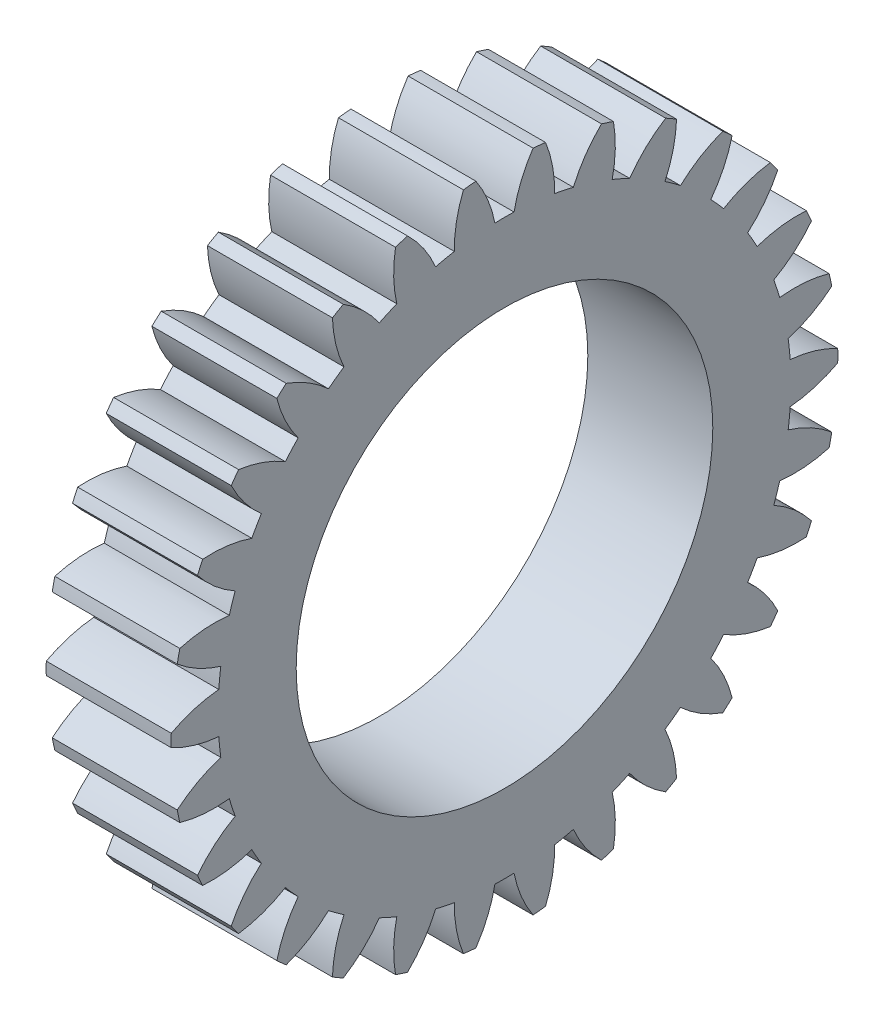
SolidWorks part; units mm, degrees
ref_plane "Plane1" through (0, 0, 0) normal (0, 0, 1) x (1, 0, 0)
ref_plane "Plane2" through (0, 0, 0) normal (0, 1, 0) x (1, 0, 0)
ref_plane "Plane3" through (0, 0, 0) normal (1, 0, 0) x (0, 0, -1)
sketch "HoldingSke" plane through (0, 0, 0) normal (0, 1, 0) x (1, 0, 0)
  line L0 (0, 0) -> (0.433, -0.25)
  line L1 (-15, 0) -> (100, 0) construction
  line L2 (0, 0) -> (-2.1039, 2.3779)
  line L3 (0, 0) -> (-11.863, 4.5341)
  line L4 (0, 0) -> (7.479, 4.318)
  line L5 (0, 0) -> (-46.8476, -17.4728)
  line L6 (0, 0) -> (-9.9476, -6.7116)
  line L7 (-2.1039, 2.3779) -> (8.6586, 51.2059)
  line L8 (-76.2, 54.61) -> (-72.9, 54.61)
  line L9 (-71.009, 38.7566) -> (-53.1078, 45.2721)
  line L10 (-76.2, 71.12) -> (104.1128, 71.12)
  line L11 (0, 0) -> (-12, 0)
  line L12 (-76.2, 101.6) -> (-76.133, 101.6)
  line L13 (24.9733, 27.94) -> (52.9518, 28.4284)
  line L14 (24.9733, 27.94) -> (24.9743, 27.94)
  line L15 (24.9733, 27.94) -> (100.4006, 29.5858)
  line L16 (-63.627, -2) -> (-12.827, -2)
  circle A0 centre (0, 0) radius 20
  circle A1 centre (0, 0) radius 27.499
  circle A2 centre (0, 0) radius 37.5
  circle A3 centre (0, 0) radius 20
  dimension "MHD" = 54.998
  dimension "Hub_dia" = 75
  dimension "Bore" = 40
  dimension "MBD" = 40
  dimension "Num_teeth" = 30
  dimension "Pitch" = 0.5
  dimension "Overall_len" = 50
  dimension "Show_teeth" = 30
  dimension "Thickness" = 12
  dimension "OAL" = 50.0001
  dimension "T_dim" = 3.3
  dimension "Ap" = 20
  dimension "H" = 19.05
  dimension "Pitch_radius" = 180.3128
  dimension "Width" = 12
  dimension "Backlash" = 0.067
  dimension "Addendum_fac" = 1
  dimension "Dedendum_fac" = 1.25
  dimension "Clearance_fac" = 0.25
  dimension "Dedendum_add" = 0.001
  dimension "Module" = 2
sketch "BasProSke" plane through (0, 0, 0) normal (0, 1, 0) x (1, 0, 0)
  line L0 (-10, 0) -> (60, 0) construction
  line L1 (0, 0) -> (0, 32)
  line L2 (0, 0) -> (12, 0)
  line L3 (12, 0) -> (12, 32)
  line L4 (12, 32) -> (0, 32)
  dimension "Thickness" = 12
  dimension "Diameter" = 64
revolve "Base-Revolve" add sketch "BasProSke" angle 360 about L0
sketch "TooCutSke" plane through (0, 0, 0) normal (1, 0, 0) x (0, 0, -1)
  line L1 (0, 0) -> (0, 107) construction
  line L2 (0, 0) -> (-1.6873, 29.9525) construction
  line L3 (0, 0) -> (-6.2643, 59.6013) construction
  line L4 (-1.6873, 29.9525) -> (-3.1322, 29.8007) construction
  arc A0 (0.9186, 27.4837) -> (-0.9186, 27.4837) centre (0, 0) ccw
  arc A1 (2.7618, 31.9061) -> (-2.7618, 31.9061) centre (0, 0) ccw
  circle A2 centre (0, 0) radius 30 construction
  circle A3 centre (0, 0) radius 28.1908 construction
  arc A4 (-0.9186, 27.4837) -> (-2.7618, 31.9061) centre (-12.6936, 25.1712) ccw
  arc A5 (2.7618, 31.9061) -> (0.9186, 27.4837) centre (12.6936, 25.1712) ccw
  dimension "Root_dia" = 54.998
  dimension "Overcut_dia" = 64.0508
  dimension "Pitch_dia" = 60
  dimension "Base_dia" = 56.3816
  dimension "Flank_rad" = 12
  dimension "Half_ang" = 6
  dimension "Half_CT" = 1.4528
extrude "ToothCut" cut sketch "TooCutSke" along normal through all
fillet "Breaks" [suppressed] radius 0.04
fillet "RootFillets" [suppressed] radius 0.501
pattern_circular "TeethCuts" count 30 every 12 about axis through (-10, 0, 0) along (1, 0, 0) of "ToothCut", "RootFillets", "Breaks"
sketch "HubNeaOneSke" plane through (0, 0, 0) normal (-1, 0, 0) x (0, 0, 1)
  circle A0 centre (0, 0) radius 27.499
  dimension "Diameter" = 54.998
extrude "HubNearOne" [suppressed] add sketch "HubNeaOneSke" along normal blind 38.0001
sketch "HubNeaBotSke" plane through (0, 0, 0) normal (-1, 0, 0) x (0, 0, 1)
  circle A0 centre (0, 0) radius 27.499
  dimension "Diameter" = 54.998
extrude "HubNearBoth" [suppressed] add sketch "HubNeaBotSke" along normal blind 19
ref_plane "FarPln" through (12, 0, 0) normal (1, 0, 0) x (0, 0, -1)
sketch "HubFarSke" plane through (12, 0, 0) normal (1, 0, 0) x (0, 0, -1)
  circle A0 centre (0, 0) radius 27.499
  dimension "Diameter" = 54.998
extrude "HubFar" [suppressed] add sketch "HubFarSke" along normal blind 19
sketch "BorSke" plane through (0, 0, 0) normal (1, 0, 0) x (0, 0, -1)
  circle A0 centre (0, 0) radius 20
  dimension "Diameter" = 40
extrude "Bore" cut sketch "BorSke" along normal mid plane 100.0001
sketch "KeySke" plane through (0, 0, 0) normal (1, 0, 0) x (0, 0, -1)
  line L0 (-6, 0) -> (-6, 23.3)
  line L1 (-6, 23.3) -> (6, 23.3)
  line L2 (6, 23.3) -> (6, 0)
  line L3 (0, 0) -> (0, 34) construction
  line L4 (-6, 0) -> (6, 0)
  dimension "Width" = 12
  dimension "Offset" = 23.3
extrude "Keyway" [suppressed] cut sketch "KeySke" along normal mid plane 100.0001
pattern_circular "Keyway2" [suppressed] count 2 every 90 about axis through (-10, 0, 0) along (1, 0, 0)
equation "' \"Module@HoldingSke\" = 6.35"
equation "' \"Num_teeth@HoldingSke\" = 12"
equation "' \"Ap@HoldingSke\" =  20"
equation "' \"Ap@HoldingSke\" = 20"
equation "' \"Width@HoldingSke\" = 0.5 * 25.4"
equation "' \"Hub_dia@HoldingSke\"= 1 * 25.4"
equation "' \"Hub_dia@HoldingSke\" = 1 * 25.4"
equation "' \"Overall_len@HoldingSke\" = 1.0 * 25.4"
equation "' \"Bore@HoldingSke\" = 0.75 * 25.4"
equation "' \"T_dim@HoldingSke\" = 0.1 * 25.4"
equation "' \"Width@KeySke\" = 0.25 * 25.4"
equation "' \"Show_teeth@HoldingSke\" = 13"
equation "' \"Backlash@HoldingSke\" = 0.009 * 25.4"
equation "' \"Addendum_fac@HoldingSke\" = 1.0"
equation "' \"Dedendum_fac@HoldingSke\" = 1.25"
equation "' \"Dedendum_add@HoldingSke\" = 0.00005 * 25.4"
equation "' \"Clearance_fac@HoldingSke\" = 0.25"
equation "\"Pitch@HoldingSke\" = 1 / \"Module@HoldingSke\""
equation "\"Overcut_dia@TooCutSke\" = (\"Num_teeth@HoldingSke\" + 2 * \"Addendum_fac@HoldingSke\") / \"Pitch@HoldingSke\" + 0.002 * 25.4"
equation "\"Pitch_dia@TooCutSke\" = \"Num_teeth@HoldingSke\" / \"Pitch@HoldingSke\""
equation "\"Base_dia@TooCutSke\" = \"Num_teeth@HoldingSke\" / \"Pitch@HoldingSke\" * cos((\"Ap@HoldingSke\"  * 3.14159265 / 180))"
equation "\"Root_dia@TooCutSke\" = (\"Num_teeth@HoldingSke\" + 2) / \"Pitch@HoldingSke\" - 2 * (\"Addendum_fac@HoldingSke\" + \"Dedendum_fac@HoldingSke\") / \"Pitch@HoldingSke\" - \"Dedendum_add@HoldingSke\" * 2"
equation "\"Half_ang@TooCutSke\" = 180 / \"Num_teeth@HoldingSke\""
equation "\"Half_CT@TooCutSke\" = \"Num_teeth@HoldingSke\" / \"Pitch@HoldingSke\" * sin((3.14159265 / 2 / \"Num_teeth@HoldingSke\")) / 2 - 7 * \"Backlash@HoldingSke\" / 4"
equation "\"Flank_rad@TooCutSke\" = \"Num_teeth@HoldingSke\" / \"Pitch@HoldingSke\" / 5"
equation "\"Radius@RootFillets\" = \"Clearance_fac@HoldingSke\" / \"Pitch@HoldingSke\" + \"Dedendum_add@HoldingSke\""
equation "\"Break_rad@Breaks\" = 0.02 / \"Pitch@HoldingSke\""
equation "\"Thickness@HoldingSke\" = \"Width@HoldingSke\""
equation "\"OAL@HoldingSke\" = \"Thickness@HoldingSke\""
equation "\"MHD@HoldingSke\" = (\"Num_teeth@HoldingSke\" + 2) / \"Pitch@HoldingSke\" - 2 * (\"Addendum_fac@HoldingSke\" + \"Dedendum_fac@HoldingSke\")  / \"Pitch@HoldingSke\" - \"Dedendum_add@HoldingSke\" * 2"
equation "\"MBD@HoldingSke\" = (\"Num_teeth@HoldingSke\" + 2) / \"Pitch@HoldingSke\" - 2 * (\"Addendum_fac@HoldingSke\" + \"Dedendum_fac@HoldingSke\")  / \"Pitch@HoldingSke\" - \"Dedendum_add@HoldingSke\" * 2 - 0.002 * 25.4"
equation "\"MHD@HoldingSke\" = ((sgn( \"MHD@HoldingSke\" - \"Hub_dia@HoldingSke\" )-1)*( \"MHD@HoldingSke\" - \"Hub_dia@HoldingSke\" ))/-2+ \"Hub_dia@HoldingSke\""
equation "\"MBD@HoldingSke\" = ((sgn( \"MBD@HoldingSke\" - \"Bore@HoldingSke\" )-1)*( \"MBD@HoldingSke\" - \"Bore@HoldingSke\" ))/-2+ \"Bore@HoldingSke\""
equation "\"OAL@HoldingSke\" = ((sgn( \"OAL@HoldingSke\" - \"Overall_len@HoldingSke\" )+1)*( \"OAL@HoldingSke\" - \"Overall_len@HoldingSke\" ))/2 + \"Overall_len@HoldingSke\" + 0.000002 * 25.4"
equation "\"Num_teeth@TeethCuts\" = int( \"Show_teeth@HoldingSke\" ) + 1"
equation "\"Num_teeth@TeethCuts\" = ((sgn( \"Num_teeth@TeethCuts\" - \"Num_teeth@HoldingSke\" )-1)*( \"Num_teeth@TeethCuts\" - \"Num_teeth@HoldingSke\" ))/-2+ \"Num_teeth@HoldingSke\""
equation "\"Num_teeth@TeethCuts\" = ((sgn( \"Num_teeth@TeethCuts\" - 2.0)+1)*( \"Num_teeth@TeethCuts\" - 2.0))/2 +2.0"
equation "\"Angle@TeethCuts\" = 360.0 / \"Num_teeth@HoldingSke\""
equation "\"Diameter@BasProSke\" = (\"Num_teeth@HoldingSke\" + 2 * \"Addendum_fac@HoldingSke\") / \"Pitch@HoldingSke\""
equation "\"Thickness@BasProSke\"  = \"Thickness@HoldingSke\""
equation "' \"Fillet_rad@BasProSke\" =  \"Thickness@HoldingSke\" * 0.05"
equation "' \"Fillet_rad@BasProSke\" = \"Thickness@HoldingSke\" * 0.05"
equation "\"MHD@HoldingSke\" = ((sgn( \"MHD@HoldingSke\" - \"Root_dia@TooCutSke\" )-1)*( \"MHD@HoldingSke\" - \"Root_dia@TooCutSke\" ))/-2+ \"Root_dia@TooCutSke\""
equation "\"Diameter@HubNeaOneSke\" = \"MHD@HoldingSke\""
equation "\"Length@HubNearOne\" = \"OAL@HoldingSke\" - \"Thickness@BasProSke\""
equation "\"Diameter@HubNeaBotSke\" = \"MHD@HoldingSke\""
equation "\"Length@HubNearBoth\" = ( \"OAL@HoldingSke\" - \"Thickness@BasProSke\" ) / 2.0"
equation "\"Thickness@FarPln\" = \"Thickness@BasProSke\""
equation "\"Diameter@HubFarSke\" = \"MHD@HoldingSke\""
equation "\"Length@HubFar\" = ( \"OAL@HoldingSke\" - \"Thickness@BasProSke\" ) / 2.0"
equation "\"Diameter@BorSke\" = \"MBD@HoldingSke\""
equation "\"D1@Bore\" = \"OAL@HoldingSke\" * 2.0"
equation "\"D1@Keyway\" = \"OAL@HoldingSke\" * 2.0"
equation "\"Offset@KeySke\" = \"T_dim@HoldingSke\" + \"MBD@HoldingSke\" / 2.0"
